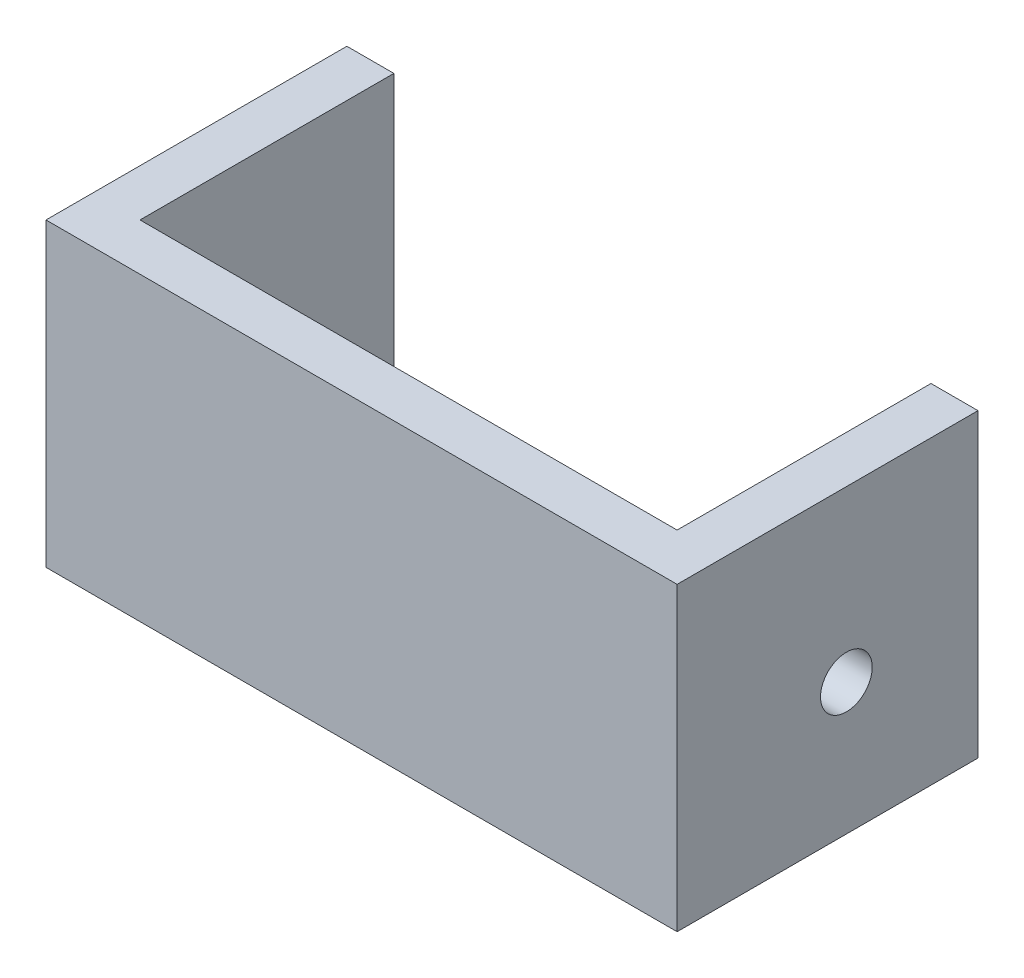
SolidWorks part; units mm, degrees
ref_plane "Front Plane" through (0, 0, 0) normal (0, 0, 1) x (1, 0, 0)
ref_plane "Top Plane" through (0, 0, 0) normal (0, 1, 0) x (1, 0, 0)
ref_plane "Right Plane" through (0, 0, 0) normal (1, 0, 0) x (0, 0, -1)
sketch "Sketch1" plane through (0, 0, 0) normal (0, 0, 1) x (1, 0, 0)
  line L1 (33.5625, 16) -> (-33.5625, 16)
  line L2 (33.5625, 16) -> (33.5625, -16)
  line L3 (33.5625, -16) -> (-33.5625, -16)
  line L4 (-33.5625, 16) -> (-33.5625, -16)
  line L5 (0, -16) -> (0, 16) construction
  line L6 (33.5625, 0) -> (-33.5625, 0) construction
  point P0 (0, 0)
  dimension "D1" = 32
  dimension "D2" = 67.125
extrude "Boss-Extrude1" add sketch "Sketch1" along normal blind 32
sketch "Sketch2" plane through (0, 0, 0) normal (0, 0, -1) x (-1, 0, 0)
  line L0 (-33.5625, 16) -> (33.5625, 16) construction
  line L1 (-28.5625, 16) -> (28.5625, 16)
  line L2 (-28.5625, 16) -> (-28.5625, -11)
  line L3 (-28.5625, -11) -> (28.5625, -11)
  line L4 (28.5625, 16) -> (28.5625, -11)
  line L5 (-33.5625, -16) -> (-33.5625, 16) construction
  line L6 (33.5625, 16) -> (33.5625, -16) construction
  line L7 (33.5625, -16) -> (-33.5625, -16) construction
  dimension "D1" = 5
  dimension "D2" = 5
  dimension "D3" = 5
extrude "Cut-Extrude1" cut sketch "Sketch2" against normal blind 27
sketch "Sketch3" plane through (33.5625, 0, 0) normal (1, 0, 0) x (0, 0, -1)
  line L2 (0, -16) -> (0, 16) construction
  line L3 (-32, -16) -> (0, -16) construction
  circle A0 centre (-14, -2) radius 2.75
  dimension "D1" = 5.5
  dimension "D2" = 14
  dimension "D3" = 14
extrude "Cut-Extrude2" cut sketch "Sketch3" against normal through all
